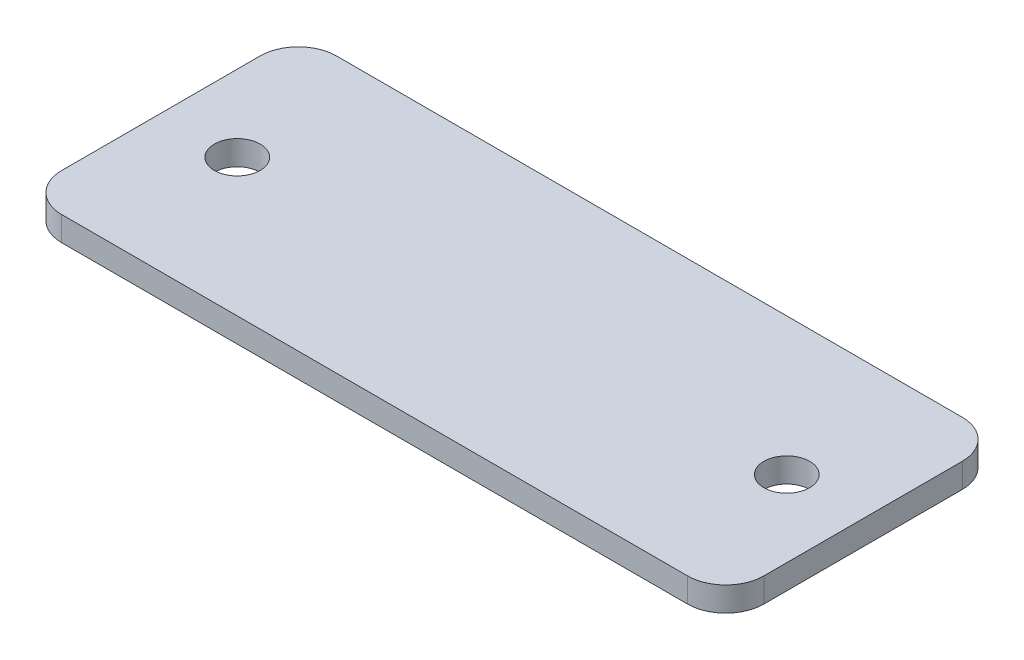
SolidWorks part; units mm, degrees
ref_plane "Alzado" through (0, 0, 0) normal (0, 0, 1) x (1, 0, 0)
ref_plane "Planta" through (0, 0, 0) normal (0, 1, 0) x (1, 0, 0)
ref_plane "Vista lateral" through (0, 0, 0) normal (1, 0, 0) x (0, 0, -1)
sketch "Sketch1" plane through (0, 0, 0) normal (0, 1, 0) x (1, 0, 0)
  line L1 (-23, -9) -> (23, -9)
  line L2 (-23, -9) -> (-23, 9)
  line L3 (-23, 9) -> (23, 9)
  line L4 (23, -9) -> (23, 9)
  line L5 (-23, -9) -> (23, 9) construction
  line L6 (-23, 9) -> (23, -9) construction
  circle A0 centre (-18, 0) radius 1.5
  circle A1 centre (18, 0) radius 1.5
  point P0 (0, 0)
  point P10 (0, 0)
  point P11 (0, 0)
  dimension "D3" = 3
  dimension "D4" = 3
  dimension "D1" = 18
  dimension "D2" = 46
  dimension "D5" = 36
  dimension "D6" = 18
extrude "Boss-Extrude1" add sketch "Sketch1" along normal blind 1.6
fillet "Fillet1" radius 2.5 4 edges at (-23, 0.8, -9) (-23, 0.8, 9) (23, 0.8, 9) (23, 0.8, -9)
